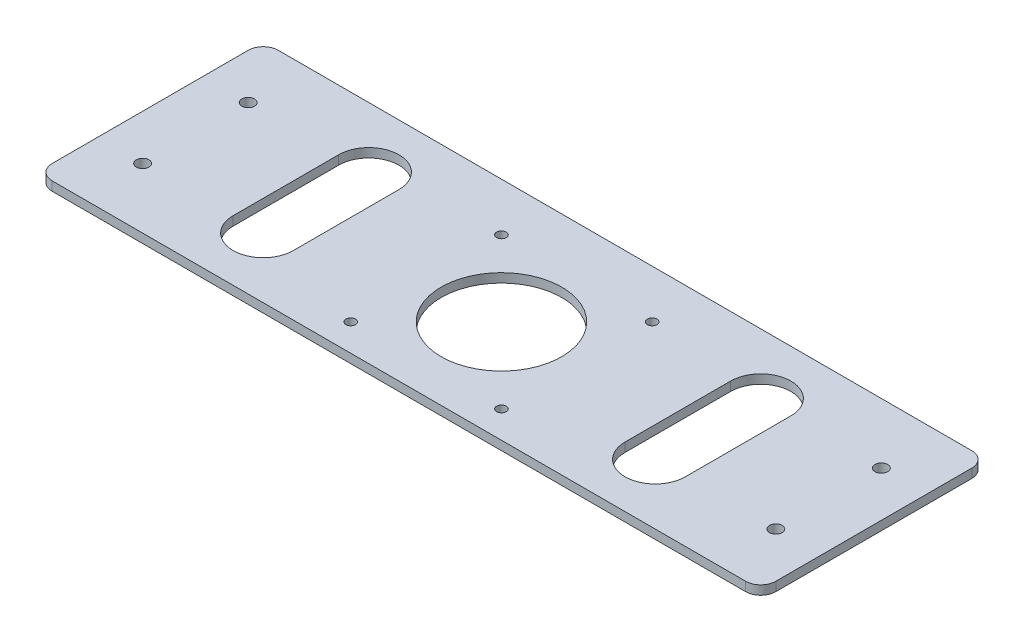
SolidWorks part; units mm, degrees
material "Thornel Mat VMA"
ref_plane "前视基准面" through (0, 0, 0) normal (0, 0, 1) x (1, 0, 0)
ref_plane "上视基准面" through (0, 0, 0) normal (0, 1, 0) x (1, 0, 0)
ref_plane "右视基准面" through (0, 0, 0) normal (1, 0, 0) x (0, 0, -1)
sketch "草图1" plane through (0, 0, 0) normal (0, 1, 0) x (1, 0, 0)
  line L0 (32.8259, -88.8718) -> (32.8259, 46.1282) construction
  line L1 (-167.1741, -13.8718) -> (232.8259, -13.8718)
  line L2 (-167.1741, -13.8718) -> (-167.1741, 46.1282)
  line L3 (-167.1741, 46.1282) -> (232.8259, 46.1282)
  line L4 (232.8259, -13.8718) -> (232.8259, 46.1282)
  line L5 (-14.6741, 36.1282) -> (80.3259, 36.1282) construction
  line L6 (-14.6741, 11.1282) -> (80.3259, 11.1282) construction
  line L7 (-87.1741, -88.8718) -> (152.8259, -88.8718)
  line L8 (-87.1741, -88.8718) -> (-87.1741, -13.8718)
  line L9 (-87.1741, -13.8718) -> (152.8259, -13.8718)
  line L10 (152.8259, -88.8718) -> (152.8259, -13.8718)
  line L11 (22.3259, 10.6282) -> (43.3259, 10.6282) construction
  line L12 (22.3259, 0.1282) -> (43.3259, 0.1282)
  line L13 (22.3259, 0.1282) -> (22.3259, 21.1282)
  line L14 (22.3259, 21.1282) -> (43.3259, 21.1282)
  line L15 (43.3259, 0.1282) -> (43.3259, 21.1282)
  line L16 (7.8259, -54.8718) -> (57.8259, -54.8718) construction
  line L17 (7.8259, -29.8718) -> (57.8259, -29.8718) construction
  line L18 (7.8259, -29.8718) -> (7.8259, -79.8718) construction
  line L19 (7.8259, -79.8718) -> (57.8259, -79.8718) construction
  line L20 (57.8259, -29.8718) -> (57.8259, -79.8718) construction
  line L21 (32.8259, 21.1282) -> (32.8259, 0.1282) construction
  line L22 (7.8259, -29.8718) -> (29.2904, -51.3362) construction
  line L23 (57.8259, -29.8718) -> (7.8259, -79.8718) construction
  line L31 (36.3615, -58.4073) -> (57.8259, -79.8718) construction
  circle A0 centre (-14.6741, 36.1282) radius 1.6
  circle A1 centre (-14.6741, 11.1282) radius 1.6
  circle A2 centre (80.3259, 11.1282) radius 1.6
  circle A3 centre (80.3259, 36.1282) radius 1.6
  circle A4 centre (7.8259, -29.8718) radius 1.6
  circle A5 centre (7.8259, -79.8718) radius 1.6
  circle A6 centre (57.8259, -79.8718) radius 1.6
  circle A7 centre (57.8259, -29.8718) radius 1.6
  circle A8 centre (32.8259, -54.8718) radius 20
  point P0 (0, 0)
  point P6 (0, -121.2547)
  point P16 (32.8259, 36.1282)
  point P19 (32.8259, 11.1282)
  point P23 (32.8259, 13.1501)
  point P30 (32.8259, -20.0664)
  point P35 (32.8259, -29.8718)
  point P44 (4.2904, -33.4073)
  point P45 (54.2904, -83.4073)
  point P46 (11.3615, -26.3362)
  point P47 (61.3615, -76.3362)
  point P48 (54.2904, -26.3362)
  point P49 (4.2904, -76.3362)
  point P50 (61.3615, -33.4073)
  point P51 (11.3615, -83.4073)
  dimension "D8" = 21
  dimension "D13" = 3.2
  dimension "D9" = 40
  dimension "D1" = 400
  dimension "D2" = 60
  dimension "D3" = 75
  dimension "D4" = 240
  dimension "D5" = 10
  dimension "D6" = 95
  dimension "D7" = 25
  dimension "D10" = 30
  dimension "D11" = 15
  dimension "D12" = 50
  dimension "D14" = 10.5
extrude "构型与裁判孔" add sketch "草图1" along normal blind 3 contours L1 L4 L3 L2 A3 L15 L12 L13 L14 A0 A1 A2 A4 A7 | L7 L10 L1 L8 A6 A5
sketch "草图2" plane through (0, 3, 0) normal (0, 1, 0) x (1, 0, 0)
  line L0 (-167.1741, 16.1282) -> (232.8259, 16.1282) construction
  line L1 (-167.1741, -13.8718) -> (-167.1741, 46.1282) construction
  line L2 (232.8259, -13.8718) -> (232.8259, 46.1282) construction
  line L3 (32.8259, 46.1282) -> (32.8259, -88.8718) construction
  line L4 (-167.1741, 46.1282) -> (232.8259, 46.1282) construction
  line L5 (-87.1741, -88.8718) -> (152.8259, -88.8718) construction
  line L6 (-149.1741, 2.6282) -> (-149.1741, 29.6282) construction
  line L7 (-121.6741, 2.6282) -> (-121.6741, 29.6282) construction
  line L8 (-149.1741, 29.6282) -> (-121.6741, 29.6282) construction
  line L9 (-51.6741, -8.8718) -> (-51.6741, 41.1282) construction
  line L10 (-135.4241, 29.6282) -> (-135.4241, 46.1282) construction
  line L11 (-135.4241, 41.1282) -> (-86.6741, 41.1282) construction
  circle A0 centre (-149.1741, 29.6282) radius 2.05
  circle A1 centre (-149.1741, 2.6282) radius 2.05
  circle A2 centre (-121.6741, 29.6282) radius 2.05
  circle A3 centre (-121.6741, 2.6282) radius 2.05
  circle A4 centre (-51.6741, 41.1282) radius 2.1
  circle A5 centre (-86.6741, 41.1282) radius 2.1
  circle A6 centre (-51.6741, -8.8718) radius 2.1
  circle A7 centre (-86.6741, -8.8718) radius 2.1
  circle A8 centre (-135.4241, 41.1282) radius 2.1
  circle A9 centre (-135.4241, -8.8718) radius 2.1
  circle A10 centre (201.0759, -8.8718) radius 2.1
  circle A11 centre (201.0759, 41.1282) radius 2.1
  circle A12 centre (152.3259, -8.8718) radius 2.1
  circle A13 centre (117.3259, -8.8718) radius 2.1
  circle A14 centre (152.3259, 41.1282) radius 2.1
  circle A15 centre (117.3259, 41.1282) radius 2.1
  circle A16 centre (187.3259, 2.6282) radius 2.05
  circle A17 centre (187.3259, 29.6282) radius 2.05
  circle A18 centre (214.8259, 2.6282) radius 2.05
  circle A19 centre (214.8259, 29.6282) radius 2.05
  point P15 (-149.1741, 16.1282)
  point P20 (-121.6741, 16.1282)
  point P25 (-51.6741, 16.1282)
  dimension "D2" = 4.1
  dimension "D4" = 5
  dimension "D5" = 4.2
  dimension "D7" = 2
  dimension "D8" = 18
  dimension "D3" = 45.5
  dimension "D1" = 27
  dimension "D6" = 70
extrude "切除-拉伸1" cut sketch "草图2" against normal through all
fillet "圆角1" radius 5 8 edges at (-167.1741, 1.5, 13.8718) (-167.1741, 1.5, -46.1282) (232.8259, 1.5, -46.1282) (232.8259, 1.5, 13.8718) (152.8259, 1.5, 13.8718) (152.8259, 1.5, 88.8718) (-87.1741, 1.5, 88.8718) (-87.1741, 1.5, 13.8718)
sketch "Sketch1" plane through (0, 0, 0) normal (0, 1, 0) x (1, 0, 0)
  line L0 (-162.1741, -13.8718) -> (-92.1741, -13.8718) construction
  line L1 (-87.1741, -83.8718) -> (-87.1741, -18.8718) construction
  line L2 (32.8259, 46.1282) -> (32.8259, -164.9495) construction
  line L3 (-162.1741, 46.1282) -> (227.8259, 46.1282) construction
  line L4 (-72.1741, -33.8718) -> (-72.1741, -68.8718) construction
  line L5 (-32.1741, -33.8718) -> (-32.1741, -68.8718) construction
  line L6 (-32.1741, -68.8718) -> (-32.1741, -33.8718) construction
  line L7 (-42.1741, -68.8718) -> (-42.1741, -33.8718)
  line L8 (-22.1741, -68.8718) -> (-22.1741, -33.8718)
  line L9 (97.8259, -68.8718) -> (97.8259, -33.8718) construction
  line L10 (107.8259, -68.8718) -> (107.8259, -33.8718)
  line L11 (87.8259, -68.8718) -> (87.8259, -33.8718)
  circle A0 centre (-72.1741, -33.8718) radius 2.1
  circle A1 centre (-72.1741, -68.8718) radius 2.1
  circle A2 centre (137.8259, -68.8718) radius 2.1
  circle A3 centre (137.8259, -33.8718) radius 2.1
  arc A4 (-42.1741, -68.8718) -> (-22.1741, -68.8718) centre (-32.1741, -68.8718) ccw
  arc A5 (-22.1741, -33.8718) -> (-42.1741, -33.8718) centre (-32.1741, -33.8718) ccw
  arc A6 (107.8259, -68.8718) -> (87.8259, -68.8718) centre (97.8259, -68.8718) cw
  arc A7 (87.8259, -33.8718) -> (107.8259, -33.8718) centre (97.8259, -33.8718) cw
  point P18 (-32.1741, -51.3718)
  point P20 (-32.1741, -51.3718)
  point P27 (97.8259, -51.3718)
  dimension "D1" = 4.2
  dimension "D2" = 20
  dimension "D3" = 35
  dimension "D4" = 15
  dimension "D5" = 15
  dimension "D7" = 10
  dimension "D6" = 40
extrude "Cut-Extrude4" cut sketch "Sketch1" along normal through all
sketch "草图3" plane through (0, 3, 0) normal (0, 1, 0) x (1, 0, 0)
  line L0 (-92.1741, -13.8718) -> (157.8259, -13.8718)
  line L1 (-87.1741, -18.8718) -> (-87.1741, -13.8718)
  line L2 (152.8259, -18.8718) -> (152.8259, -13.8718)
  line L9 (-167.1741, 41.1282) -> (-167.1741, -8.8718)
  line L10 (-162.1741, -13.8718) -> (-92.1741, -13.8718)
  line L11 (-87.1741, -18.8718) -> (-87.1741, -83.8718)
  line L12 (-82.1741, -88.8718) -> (147.8259, -88.8718)
  line L13 (152.8259, -83.8718) -> (152.8259, -18.8718)
  line L14 (157.8259, -13.8718) -> (227.8259, -13.8718)
  line L15 (232.8259, -8.8718) -> (232.8259, 41.1282)
  line L16 (227.8259, 46.1282) -> (-162.1741, 46.1282)
  line L17 (-167.1741, 41.1282) -> (-167.1741, -8.8718)
  line L18 (-162.1741, -13.8718) -> (-92.1741, -13.8718)
  line L19 (-87.1741, -18.8718) -> (-87.1741, -83.8718)
  line L20 (-82.1741, -88.8718) -> (147.8259, -88.8718)
  line L21 (152.8259, -83.8718) -> (152.8259, -18.8718)
  line L22 (157.8259, -13.8718) -> (227.8259, -13.8718)
  line L23 (232.8259, -8.8718) -> (232.8259, 41.1282)
  line L24 (227.8259, 46.1282) -> (-162.1741, 46.1282)
  arc A9 (-167.1741, -8.8718) -> (-162.1741, -13.8718) centre (-162.1741, -8.8718) ccw
  arc A10 (-87.1741, -18.8718) -> (-92.1741, -13.8718) centre (-92.1741, -18.8718) ccw
  arc A11 (-87.1741, -83.8718) -> (-82.1741, -88.8718) centre (-82.1741, -83.8718) ccw
  arc A12 (147.8259, -88.8718) -> (152.8259, -83.8718) centre (147.8259, -83.8718) ccw
  arc A13 (157.8259, -13.8718) -> (152.8259, -18.8718) centre (157.8259, -18.8718) ccw
  arc A14 (227.8259, -13.8718) -> (232.8259, -8.8718) centre (227.8259, -8.8718) ccw
  arc A15 (232.8259, 41.1282) -> (227.8259, 46.1282) centre (227.8259, 41.1282) ccw
  arc A16 (-162.1741, 46.1282) -> (-167.1741, 41.1282) centre (-162.1741, 41.1282) ccw
  arc A17 (-167.1741, -8.8718) -> (-162.1741, -13.8718) centre (-162.1741, -8.8718) ccw
  arc A18 (-87.1741, -18.8718) -> (-92.1741, -13.8718) centre (-92.1741, -18.8718) ccw
  arc A19 (-87.1741, -83.8718) -> (-82.1741, -88.8718) centre (-82.1741, -83.8718) ccw
  arc A20 (147.8259, -88.8718) -> (152.8259, -83.8718) centre (147.8259, -83.8718) ccw
  arc A21 (157.8259, -13.8718) -> (152.8259, -18.8718) centre (157.8259, -18.8718) ccw
  arc A22 (227.8259, -13.8718) -> (232.8259, -8.8718) centre (227.8259, -8.8718) ccw
  arc A23 (232.8259, 41.1282) -> (227.8259, 46.1282) centre (227.8259, 41.1282) ccw
  arc A24 (-162.1741, 46.1282) -> (-167.1741, 41.1282) centre (-162.1741, 41.1282) ccw
  dimension "D1" = 0
extrude "切除-拉伸2" cut sketch "草图3" against normal blind 10 contours L24 A24 L17 A17 L18 L0 L22 A22 L23 A23 | A18 L1 L0 | A21 L0 L2
fillet "圆角2" radius 5 2 edges at (-87.1741, 1.5, 13.8718) (152.8259, 1.5, 13.8718)
